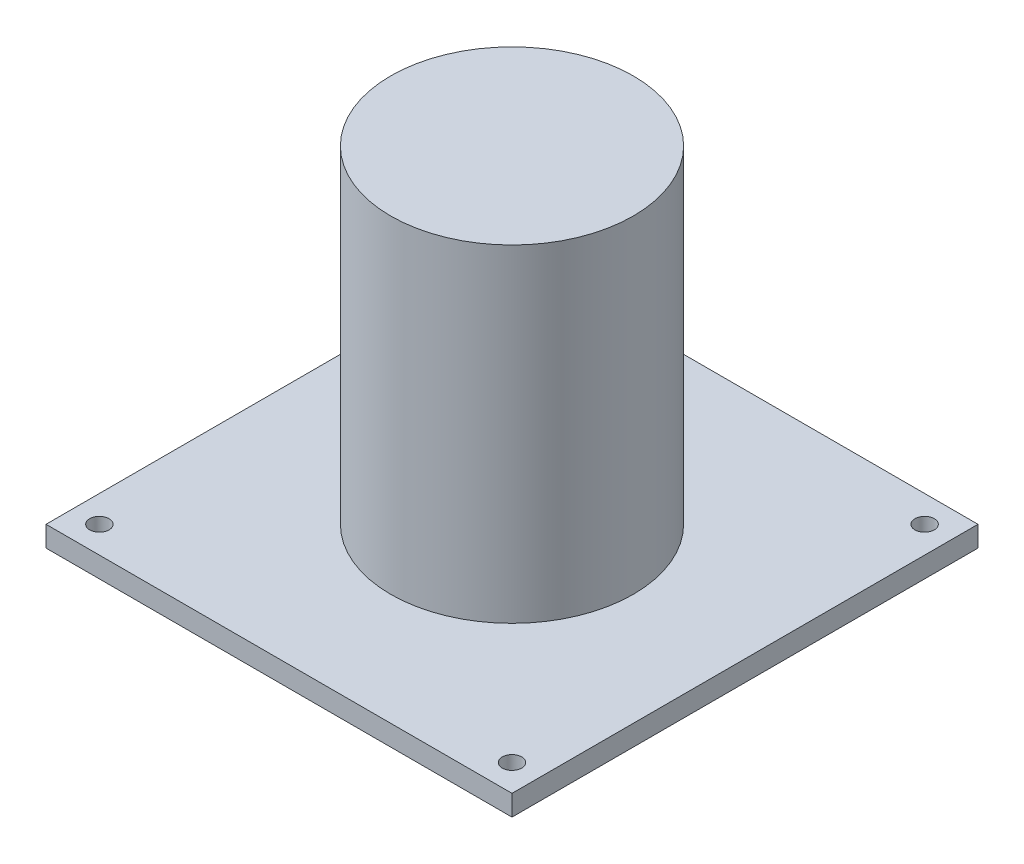
SolidWorks part; units mm, degrees
ref_plane "前视基准面" through (0, 0, 0) normal (0, 0, 1) x (1, 0, 0)
ref_plane "上视基准面" through (0, 0, 0) normal (0, 1, 0) x (1, 0, 0)
ref_plane "右视基准面" through (0, 0, 0) normal (1, 0, 0) x (0, 0, -1)
sketch "草图1" plane through (0, 0, 0) normal (0, 1, 0) x (1, 0, 0)
  line L1 (-19.2, -19.2) -> (19.2, -19.2)
  line L2 (-19.2, -19.2) -> (-19.2, 19.2)
  line L3 (-19.2, 19.2) -> (19.2, 19.2)
  line L4 (19.2, -19.2) -> (19.2, 19.2)
  line L5 (-19.2, -19.2) -> (19.2, 19.2) construction
  line L6 (-19.2, 19.2) -> (19.2, -19.2) construction
  point P0 (0, 0)
  dimension "D1" = 38.4
  dimension "D2" = 38.4
extrude "凸台-拉伸1" add sketch "草图1" along normal blind 1.7
sketch "草图2" plane through (0, 1.7, 0) normal (0, 1, 0) x (1, 0, 0)
  circle A0 centre (0, 0) radius 10
  dimension "D1" = 20
extrude "凸台-拉伸2" add sketch "草图2" along normal blind 27
sketch "草图3" plane through (0, 0, 0) normal (0, -1, 0) x (1, 0, 0)
  line L1 (-17, -17) -> (17, -17) construction
  line L2 (-17, -17) -> (-17, 17) construction
  line L3 (-17, 17) -> (17, 17) construction
  line L4 (17, -17) -> (17, 17) construction
  line L5 (-17, -17) -> (17, 17) construction
  line L6 (-17, 17) -> (17, -17) construction
  circle A0 centre (-17, 17) radius 0.8
  circle A1 centre (17, 17) radius 0.8
  circle A2 centre (17, -17) radius 0.8
  circle A3 centre (-17, -17) radius 0.8
  point P0 (0, 0)
  dimension "D3" = 1.6
  dimension "D4" = 1.6
  dimension "D5" = 1.6
  dimension "D6" = 1.6
  dimension "D1" = 34
  dimension "D2" = 34
extrude "切除-拉伸1" cut sketch "草图3" against normal blind 10
